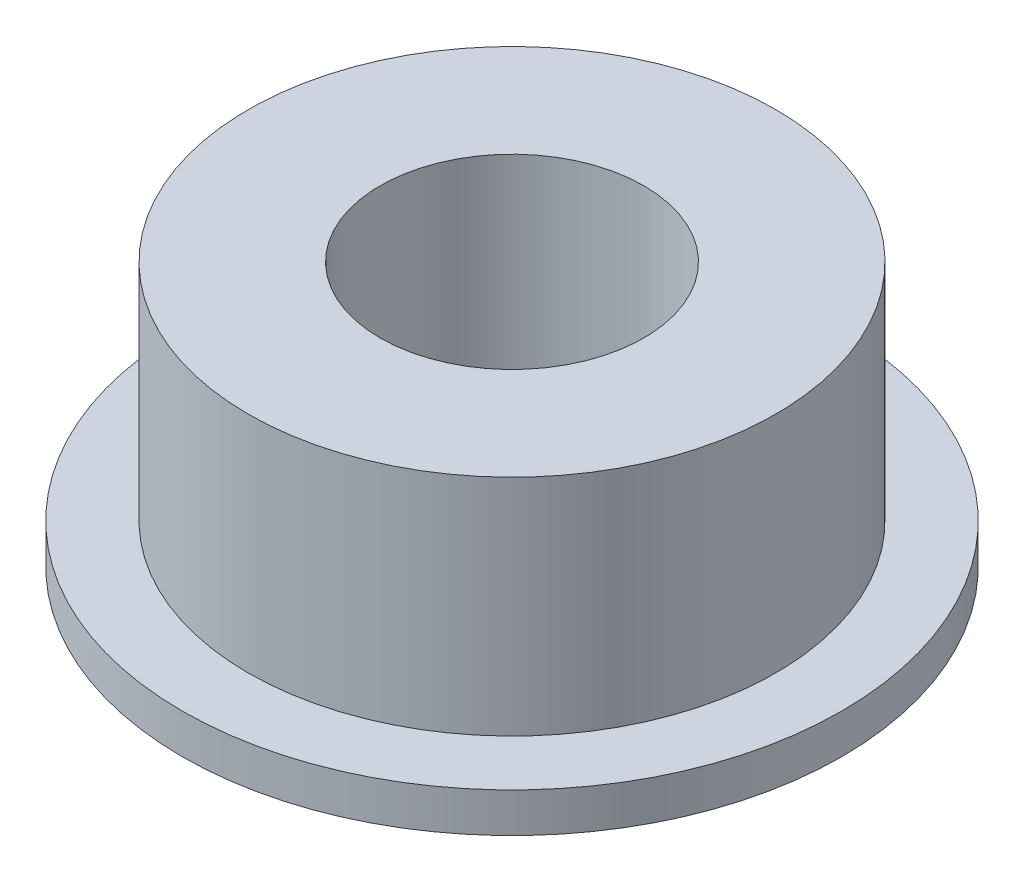
SolidWorks part; units mm, degrees
ref_plane "前视基准面" through (0, 0, 0) normal (0, 0, 1) x (1, 0, 0)
ref_plane "上视基准面" through (0, 0, 0) normal (0, 1, 0) x (1, 0, 0)
ref_plane "右视基准面" through (0, 0, 0) normal (1, 0, 0) x (0, 0, -1)
sketch "草图1" plane through (0, 0, 0) normal (0, 1, 0) x (1, 0, 0)
  circle A0 centre (0, 0) radius 4
  circle A1 centre (0, 0) radius 2
  dimension "D1" = 8
  dimension "D2" = 4
extrude "凸台-拉伸1" add sketch "草图1" along normal blind 3
sketch "草图2" plane through (0, 0, 0) normal (0, -1, 0) x (1, 0, 0)
  circle A0 centre (0, 0) radius 5
  circle A1 centre (0, 0) radius 2 construction
  circle A2 centre (0, 0) radius 2
  dimension "D1" = 10
extrude "凸台-拉伸2" add sketch "草图2" against normal blind 0.6
sketch "草图3" plane through (0, 3, 0) normal (0, 1, 0) x (1, 0, 0)
  circle A0 centre (0, 0) radius 2 construction
  circle A1 centre (0, 0) radius 4
  circle A2 centre (0, 0) radius 4
  circle A3 centre (0, 0) radius 2
  dimension "D1" = 0
extrude "凸台-拉伸3" add sketch "草图3" along normal blind 1
